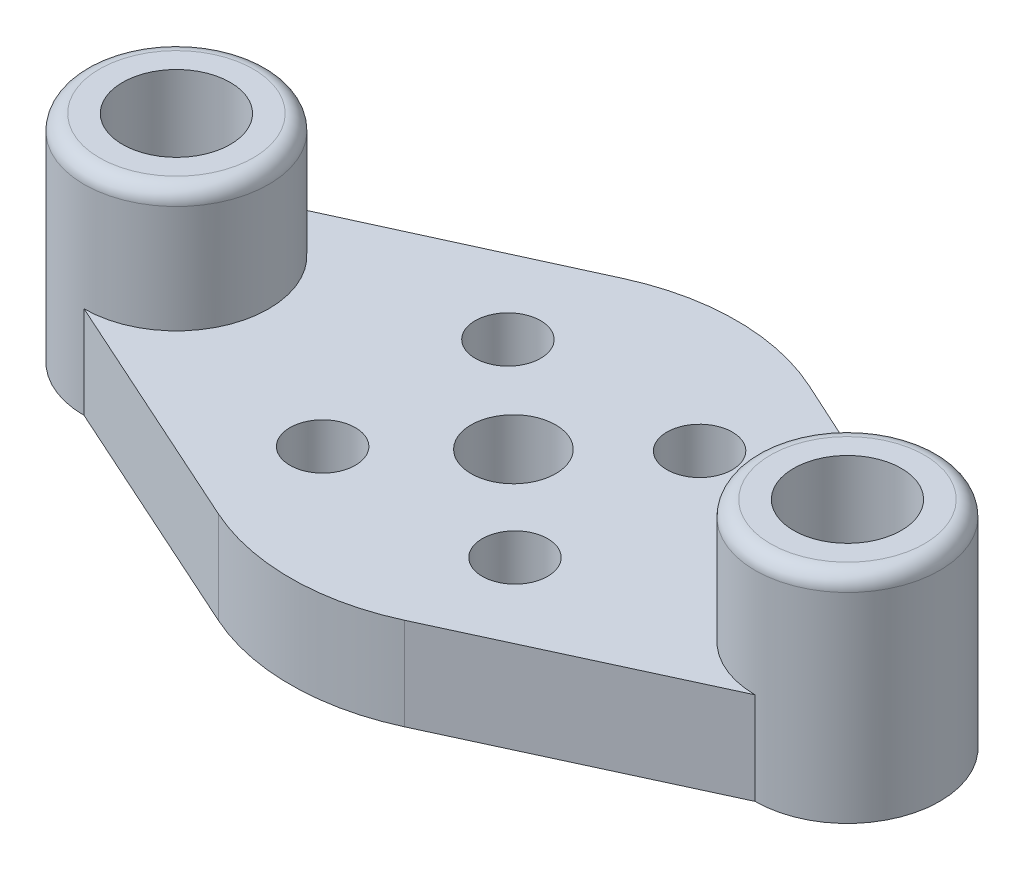
SolidWorks part; units mm, degrees
ref_plane "Plano frontal" through (0, 0, 0) normal (0, 0, 1) x (1, 0, 0)
ref_plane "Plano superior" through (0, 0, 0) normal (0, 1, 0) x (1, 0, 0)
ref_plane "Plano direito" through (0, 0, 0) normal (1, 0, 0) x (0, 0, -1)
sketch "Esboço2" plane through (0, 0, 0) normal (0, 1, 0) x (1, 0, 0)
  line L7 (-43.7089, 11.9045) -> (-12.0576, 26.3745)
  line L8 (12.0576, 26.3745) -> (43.3534, 12.067)
  line L10 (-43.7089, -12.0955) -> (-11.9258, -26.4344)
  line L11 (43.3534, -11.933) -> (12.151, -26.3316)
  circle A0 centre (-43.7089, -0.0955) radius 12
  circle A1 centre (43.3534, 0.067) radius 12
  arc A2 (-11.9258, -26.4344) -> (12.151, -26.3316) centre (0, 0) ccw
  arc A3 (12.0576, 26.3745) -> (-12.0576, 26.3745) centre (0, 0) ccw
  circle A4 centre (12.2851, 11.9176) radius 4.25
  circle A5 centre (-12.7148, 12.0007) radius 4.25
  circle A6 centre (-12.7149, -12.0824) radius 4.25
  circle A7 centre (12.2851, -12.0824) radius 4.25
  circle A8 centre (0, 0) radius 5.5
  circle A9 centre (-43.7089, -0.0955) radius 7
  circle A10 centre (43.3534, 0.067) radius 7
  dimension "D3" = 24
  dimension "D4" = 24
  dimension "D5" = 58
  dimension "D6" = 8.5
  dimension "D7" = 8.5
  dimension "D8" = 8.5
  dimension "D9" = 8.5
  dimension "D10" = 11
  dimension "D11" = 14
  dimension "D12" = 14
  dimension "D1" = 25
  dimension "D2" = 87.0625
extrude "Ressalto-extrusão2" add sketch "Esboço2" along normal blind 12 contours A0 | L8 A3 L7 A0 L10 A2 L11 A1 A8 A7 A6 A5 A4 | A1
sketch "Esboço3" plane through (0, 12, 0) normal (0, 1, 0) x (1, 0, 0)
  circle A0 centre (-43.7089, -0.0955) radius 12
  circle A1 centre (43.3534, 0.067) radius 12
  circle A2 centre (-43.7089, -0.0955) radius 7
  circle A3 centre (43.3534, 0.067) radius 7
extrude "Ressalto-extrusão3" add sketch "Esboço3" along normal blind 16
fillet "Filete1" radius 2 2 edges at (43.3534, 28, 11.933) (-43.7089, 28, 12.0955)
